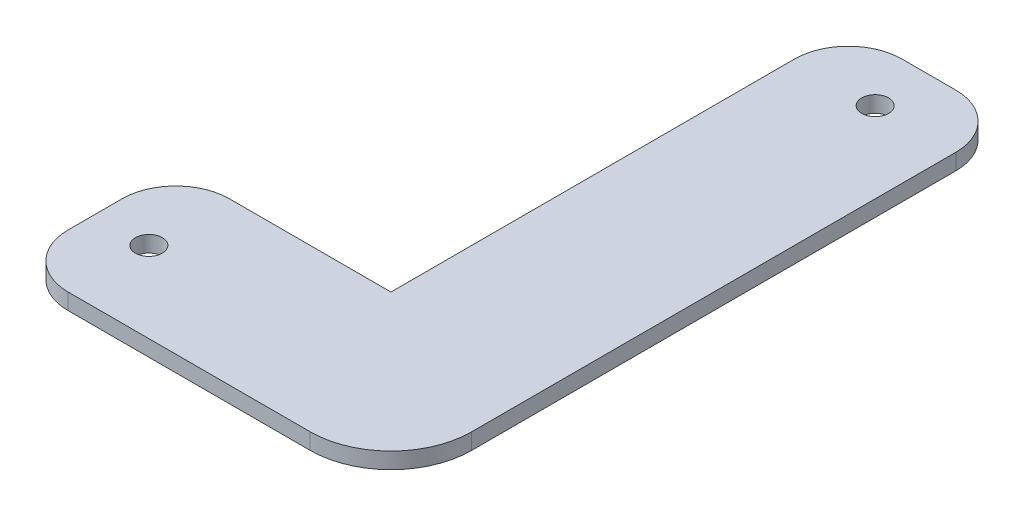
SolidWorks part; units mm, degrees
ref_plane "Front Plane" through (0, 0, 0) normal (0, 0, 1) x (1, 0, 0)
ref_plane "Top Plane" through (0, 0, 0) normal (0, 1, 0) x (1, 0, 0)
ref_plane "Right Plane" through (0, 0, 0) normal (1, 0, 0) x (0, 0, -1)
sketch "Sketch1" plane through (0, 0, 0) normal (0, 1, 0) x (1, 0, 0)
  line L4 (0, 115) -> (-30, 115)
  line L5 (-30, 30) -> (-30, 115)
  line L7 (-30, 30) -> (-70, 30)
  line L9 (0, 0) -> (-70, 0)
  line L10 (-70, 30) -> (-70, 0)
  line L20 (0, 115) -> (0, 0)
  point P0 (-70, 15)
  dimension "D3" = 30
  dimension "D1" = 30
  dimension "D2" = 40
  dimension "D4" = 100
extrude "Boss-Extrude1" add sketch "Sketch1" along normal blind 3
fillet "Fillet1" radius 10 4 edges at (-70, 1.5, 0) (-70, 1.5, -30) (0, 1.5, -115) (-30, 1.5, -115)
fillet "Fillet2" radius 15 1 edges at (0, 1.5, 0)
sketch "Sketch2" plane through (0, 3, 0) normal (0, 1, 0) x (1, 0, 0)
  line L0 (0, 105) -> (0, 15) construction
  line L1 (-10, 115) -> (-20, 115) construction
  circle A0 centre (-60, 15) radius 2.5
  circle A1 centre (-15, 105) radius 2.5
  point P2 (-60, 15)
  point P5 (-15, 105)
  point P10 (-15, 152.7062)
  dimension "D1" = 60
  dimension "D3" = 5
  dimension "D2" = 15
  dimension "D4" = 15
  dimension "D5" = 10
extrude "Cut-Extrude1" cut sketch "Sketch2" against normal through all
